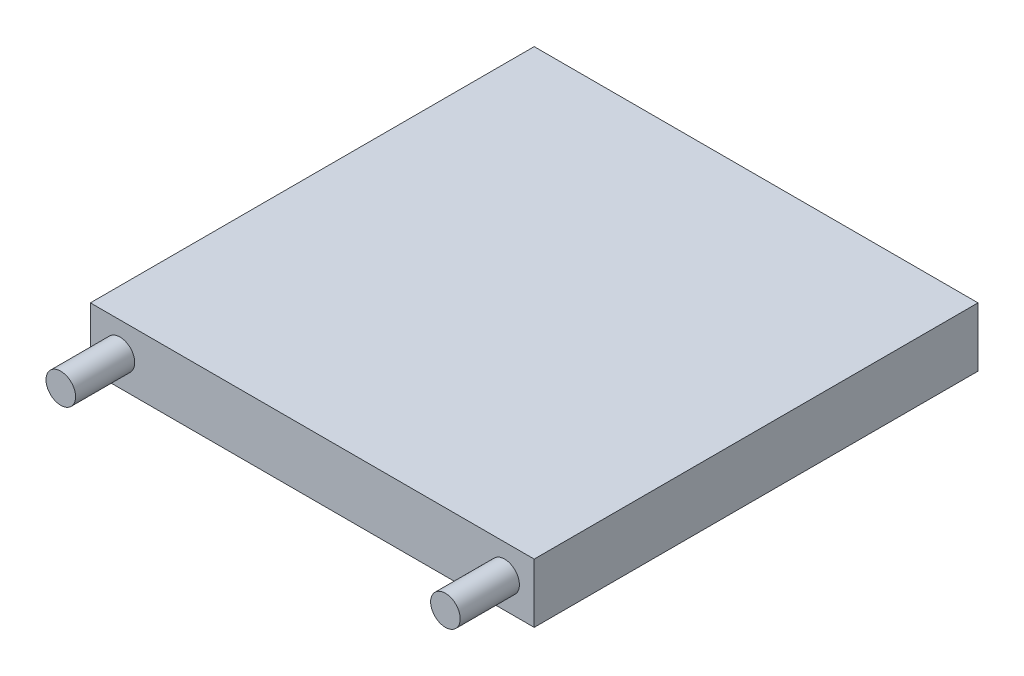
SolidWorks part; units mm, degrees
ref_plane "Front Plane" through (0, 0, 0) normal (0, 0, 1) x (1, 0, 0)
ref_plane "Top Plane" through (0, 0, 0) normal (0, 1, 0) x (1, 0, 0)
ref_plane "Right Plane" through (0, 0, 0) normal (1, 0, 0) x (0, 0, -1)
sketch "Sketch1" plane through (0, 0, 0) normal (0, 1, 0) x (1, 0, 0)
  line L1 (-15, -15) -> (15, -15)
  line L2 (-15, -15) -> (-15, 15)
  line L3 (-15, 15) -> (15, 15)
  line L4 (15, -15) -> (15, 15)
  line L5 (-15, -15) -> (15, 15) construction
  line L6 (-15, 15) -> (15, -15) construction
  point P0 (0, 0)
  dimension "D1" = 30
  dimension "D2" = 30
extrude "Boss-Extrude1" add sketch "Sketch1" along normal blind 4
sketch "Sketch2" plane through (0, 0, 15) normal (0, 0, 1) x (1, 0, 0)
  line L1 (-15, 4) -> (-15, 0) construction
  line L2 (0, 0) -> (0, 7.4727) construction
  circle A0 centre (-13, 2) radius 1
  circle A1 centre (13, 2) radius 1
  dimension "D1" = 2
  dimension "D2" = 2
extrude "Boss-Extrude2" add sketch "Sketch2" along normal blind 4
